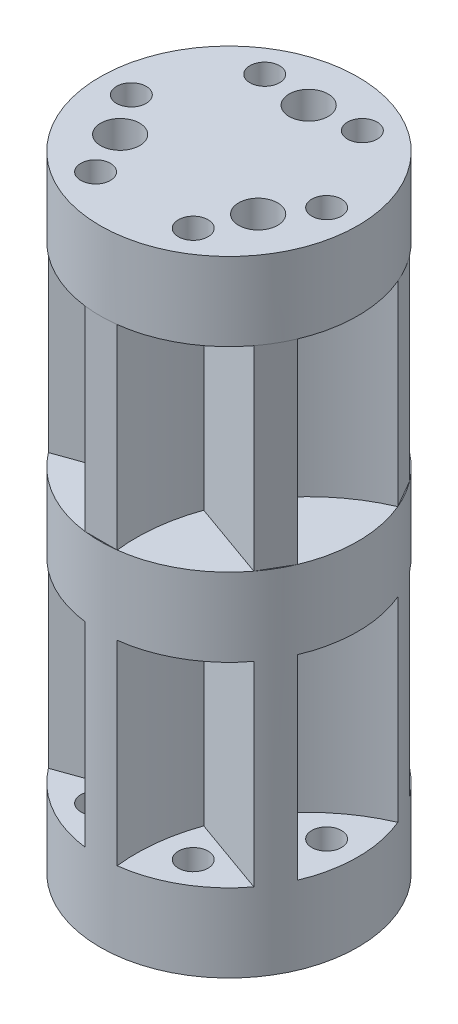
SolidWorks part; units mm, degrees
ref_plane "前视基准面" through (0, 0, 0) normal (0, 0, 1) x (1, 0, 0)
ref_plane "上视基准面" through (0, 0, 0) normal (0, 1, 0) x (1, 0, 0)
ref_plane "右视基准面" through (0, 0, 0) normal (1, 0, 0) x (0, 0, -1)
other "Configuration Table"
sketch "草图1" plane through (0, 0, 0) normal (0, 1, 0) x (1, 0, 0)
  line L0 (0, 0) -> (0, 12.5) construction
  line L1 (0, 0) -> (0, -12.5) construction
  line L2 (0, 0) -> (-6.25, 10.8253)
  circle A0 centre (0, 0) radius 10.2
  circle A1 centre (0, 0) radius 12.5
  circle A4 centre (0, 0) radius 16.5
  dimension "D1" = 20.4
  dimension "D2" = 25
  dimension "D4" = 30
  dimension "D5" = 33
extrude "凸台-拉伸1" add sketch "草图1" along normal blind 10 contours A4
sketch "草图4" plane through (0, 10, 0) normal (0, 1, 0) x (1, 0, 0)
  line L0 (0, -10.2) -> (0, 10.2) construction
  line L1 (0, 0) -> (-6.25, 10.8253)
  circle A0 centre (0, 0) radius 10.2
  circle A1 centre (0, 0) radius 12.5
  circle A2 centre (0, 10.2) radius 2.5
  circle A3 centre (-6.25, 10.8253) radius 1.9
  circle A4 centre (6.25, 10.8253) radius 1.9
  circle A5 centre (12.5, 0) radius 1.9
  circle A6 centre (6.25, -10.8253) radius 1.9
  circle A7 centre (-6.25, -10.8253) radius 1.9
  circle A8 centre (-12.5, 0) radius 1.9
  circle A9 centre (8.8335, -5.1) radius 2.5
  circle A10 centre (-8.8335, -5.1) radius 2.5
  point P23 (0, 0)
  point P28 (0, 0)
  dimension "D1" = 20.4
  dimension "D2" = 25
  dimension "D4" = 3.8
  dimension "D5" = 5
  dimension "D3" = 30
  dimension "D6" = 6
  dimension "D7" = 3
extrude "切除-拉伸1" cut sketch "草图4" against normal through all and the other way through all contours A8 | A3 | A2 | A10 | A7 | A6 | A9 | A5 | A4
sketch "草图6" plane through (0, 10, 0) normal (0, 1, 0) x (1, 0, 0)
  line L0 (14.2894, 8.25) -> (-14.2894, -8.25) construction
  line L1 (0, 0) -> (8.8335, -5.1) construction
  line L2 (0, 0) -> (0, 10.2) construction
  line L3 (-15.2062, -6.4048) -> (-7.1456, 0.4491)
  line L4 (-13.1498, -9.9666) -> (-3.1839, -6.4128)
  line L5 (2.0564, 16.3714) -> (3.9617, 5.9637)
  line L6 (-2.0564, 16.3714) -> (-3.9617, 5.9637)
  line L7 (13.1498, -9.9666) -> (3.1839, -6.4128)
  line L8 (15.2062, -6.4048) -> (7.1456, 0.4491)
  arc A0 (-2.0564, -16.3714) -> (-3.1839, -6.4128) centre (-23.9058, -13.802) ccw
  circle A1 centre (0, 0) radius 16.5 construction
  arc A2 (-13.1498, 9.9666) -> (-3.9617, 5.9637) centre (0, 27.6041) ccw
  arc A3 (15.2062, 6.4048) -> (7.1456, 0.4491) centre (23.9058, -13.802) ccw
  arc A4 (-13.1498, 9.9666) -> (-15.2062, 6.4048) centre (0, 0) ccw
  arc A7 (-7.1456, 0.4491) -> (-15.2062, 6.4048) centre (-23.9058, -13.802) ccw
  arc A8 (15.2062, 6.4048) -> (13.1498, 9.9666) centre (0, 0) ccw
  arc A9 (2.0564, 16.3714) -> (-2.0564, 16.3714) centre (0, 0) ccw
  arc A10 (-2.0564, -16.3714) -> (2.0564, -16.3714) centre (0, 0) ccw
  arc A11 (-15.2062, -6.4048) -> (-13.1498, -9.9666) centre (0, 0) ccw
  arc A12 (13.1498, -9.9666) -> (15.2062, -6.4048) centre (0, 0) ccw [skipped]
  arc A13 (2.0564, 16.3714) -> (-2.0564, 16.3714) centre (0, 0) ccw [skipped]
  arc A14 (13.1498, -9.9666) -> (15.2062, -6.4048) centre (0, 0) ccw
  arc A15 (3.1839, -6.4128) -> (2.0564, -16.3714) centre (23.9058, -13.802) ccw
  arc A16 (3.9617, 5.9637) -> (13.1498, 9.9666) centre (0, 27.6041) ccw
  point P20 (0, 0)
  point P22 (0, 0)
  point P25 (0, 0)
  point P37 (0, 0)
  point P43 (0, 0)
  dimension "D4" = 6
  dimension "D2" = 3
  dimension "D1" = 3
extrude "凸台-拉伸2" add sketch "草图6" along normal blind 25
sketch "草图7" plane through (0, 35, 0) normal (0, 1, 0) x (1, 0, 0)
  circle A0 centre (0, 0) radius 16.5
extrude "凸台-拉伸3" add sketch "草图7" along normal blind 5
mirror "镜向3" about plane through (0, 40, 0) normal (0, 1, 0) of "凸台-拉伸3"
sketch "草图9" plane through (0, 45, 0) normal (0, 1, 0) x (1, 0, 0)
  line L0 (-13.1498, -9.9666) -> (-3.1839, -6.4128) construction
  line L1 (3.1839, -6.4128) -> (13.1498, -9.9666) construction
  line L2 (15.2062, -6.4048) -> (7.1456, 0.4491) construction
  line L3 (3.9617, 5.9637) -> (2.0564, 16.3714) construction
  line L4 (-2.0564, 16.3714) -> (-3.9617, 5.9637) construction
  line L5 (-7.1456, 0.4491) -> (-15.2062, -6.4048) construction
  line L6 (-13.1498, -9.9666) -> (-3.1839, -6.4128)
  line L7 (3.1839, -6.4128) -> (13.1498, -9.9666)
  line L8 (15.2062, -6.4048) -> (7.1456, 0.4491)
  line L9 (3.9617, 5.9637) -> (2.0564, 16.3714)
  line L10 (-2.0564, 16.3714) -> (-3.9617, 5.9637)
  line L11 (-7.1456, 0.4491) -> (-15.2062, -6.4048)
  line L12 (2.0564, 16.3714) -> (-2.0564, 16.3714)
  line L13 (-13.1498, 9.9666) -> (-15.2062, 6.4048)
  line L14 (-15.2062, -6.4048) -> (-13.1498, -9.9666)
  line L15 (-2.0564, -16.3714) -> (2.0564, -16.3714)
  line L16 (13.1498, -9.9666) -> (15.2062, -6.4048)
  line L17 (13.1498, 9.9666) -> (15.2062, 6.4048)
  arc A0 (-2.0564, -16.3714) -> (-3.1839, -6.4128) centre (-23.9058, -13.802) ccw construction
  arc A1 (3.1839, -6.4128) -> (2.0564, -16.3714) centre (23.9058, -13.802) ccw construction
  arc A2 (15.2062, 6.4048) -> (7.1456, 0.4491) centre (23.9058, -13.802) ccw construction
  arc A3 (3.9617, 5.9637) -> (13.1498, 9.9666) centre (0, 27.6041) ccw construction
  arc A4 (-13.1498, 9.9666) -> (-3.9617, 5.9637) centre (0, 27.6041) ccw construction
  arc A5 (-7.1456, 0.4491) -> (-15.2062, 6.4048) centre (-23.9058, -13.802) ccw construction
  arc A6 (-2.0564, -16.3714) -> (-3.1839, -6.4128) centre (-23.9058, -13.802) ccw
  arc A7 (3.1839, -6.4128) -> (2.0564, -16.3714) centre (23.9058, -13.802) ccw
  arc A8 (15.2062, 6.4048) -> (7.1456, 0.4491) centre (23.9058, -13.802) ccw
  arc A9 (3.9617, 5.9637) -> (13.1498, 9.9666) centre (0, 27.6041) ccw
  arc A10 (-13.1498, 9.9666) -> (-3.9617, 5.9637) centre (0, 27.6041) ccw
  arc A11 (-7.1456, 0.4491) -> (-15.2062, 6.4048) centre (-23.9058, -13.802) ccw
extrude "凸台-拉伸4" add sketch "草图9" along normal blind 25
sketch "草图10" plane through (0, 70, 0) normal (0, 1, 0) x (1, 0, 0)
  circle A0 centre (0, 0) radius 16.5
extrude "凸台-拉伸5" add sketch "草图10" along normal blind 10
sketch "草图11" plane through (0, 80, 0) normal (0, 1, 0) x (1, 0, 0)
  circle A0 centre (12.5, 0) radius 1.9 construction
  circle A1 centre (8.8335, -5.1) radius 2.5 construction
  circle A2 centre (6.25, -10.8253) radius 1.9 construction
  circle A3 centre (-6.25, -10.8253) radius 1.9 construction
  circle A4 centre (-8.8335, -5.1) radius 2.5 construction
  circle A5 centre (-12.5, 0) radius 1.9 construction
  circle A6 centre (-6.25, 10.8253) radius 1.9 construction
  circle A7 centre (0, 10.2) radius 2.5 construction
  circle A8 centre (6.25, 10.8253) radius 1.9 construction
  circle A9 centre (12.5, 0) radius 1.9
  circle A10 centre (8.8335, -5.1) radius 2.5
  circle A11 centre (6.25, -10.8253) radius 1.9
  circle A12 centre (-6.25, -10.8253) radius 1.9
  circle A13 centre (-8.8335, -5.1) radius 2.5
  circle A14 centre (-12.5, 0) radius 1.9
  circle A15 centre (-6.25, 10.8253) radius 1.9
  circle A16 centre (0, 10.2) radius 2.5
  circle A17 centre (6.25, 10.8253) radius 1.9
extrude "切除-拉伸3" cut sketch "草图11" against normal blind 10
